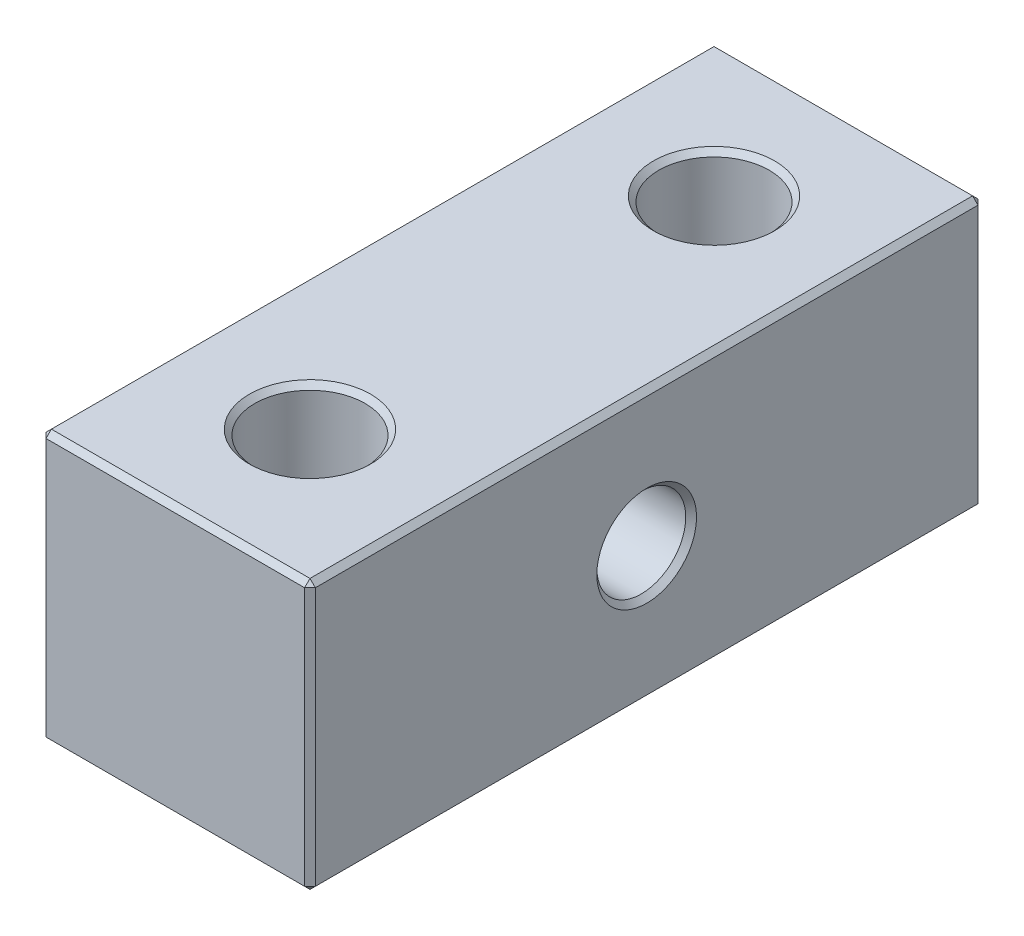
SolidWorks part; units mm, degrees
ref_plane "前视基准面" through (0, 0, 0) normal (0, 0, 1) x (1, 0, 0)
ref_plane "上视基准面" through (0, 0, 0) normal (0, 1, 0) x (1, 0, 0)
ref_plane "右视基准面" through (0, 0, 0) normal (1, 0, 0) x (0, 0, -1)
sketch "草图1" plane through (0, 0, 0) normal (0, 0, 1) x (1, 0, 0)
  line L1 (-5, 5) -> (5, 5)
  line L2 (-5, 5) -> (-5, -5)
  line L3 (-5, -5) -> (5, -5)
  line L4 (5, 5) -> (5, -5)
  line L5 (-5, 5) -> (5, -5) construction
  line L6 (-5, -5) -> (5, 5) construction
  point P0 (0, 0)
  dimension "D1" = 10
extrude "凸台-拉伸1" add sketch "草图1" along normal mid plane 25
hole_wizard "M4 螺纹孔1" positions "草图2" profile "草图3" tap size "M4" standard "GB" end condition through all
sketch "草图2" plane through (5, 0, 0) normal (1, 0, 0) x (0, 0, -1)
  line L0 (0, 0) -> (50000, 0) construction
  line L1 (12.5, -5) -> (12.5, 5) construction
  point P0 (0, 0)
  point P7 (0, 0)
  dimension "D1" = 12.5
sketch "草图3" plane through (5, 0, 0) normal (0, 1, 0) x (0, 0, -1)
  line L0 (0, 0) -> (0, 10)
  line L1 (0, 10) -> (1.65, 10)
  line L2 (1.65, 10) -> (1.65, 0)
  line L5 (1.65, 0) -> (0, 0)
  line L11 (0, -6.35) -> (0, 107.95) construction
  dimension "通孔螺纹孔钻头直径" = 3.3
  dimension "通孔螺纹孔钻头深度" = 10
cosmetic thread "孔螺蚊线3" parameters "D2"=4
hole_wizard "Ø4.1 (4.1) 直径孔1" positions "草图6" profile "草图7" hole size "Ø4.1" standard "GB" end condition through all
sketch "草图6" plane through (0, 5, 0) normal (0, 1, 0) x (1, 0, 0)
  line L0 (0, 0) -> (0, 50000) construction
  line L1 (0, 0) -> (50000, 0) construction
  point P0 (0, -7.5)
  point P2 (0, 7.5)
  point P11 (0, 0)
  point P12 (0, 0)
  point P15 (0, 0)
  dimension "D1" = 15
sketch "草图7" plane through (0, 5, 7.5) normal (1, 0, 0) x (0, 0, 1)
  line L0 (0, 0) -> (0, 10)
  line L1 (0, 10) -> (2.05, 10)
  line L2 (2.05, 10) -> (2.05, 0)
  line L5 (2.05, 0) -> (0, 0)
  line L11 (0, -6.35) -> (0, 107.95) construction
  dimension "通孔孔直径" = 4.1
  dimension "通孔孔深度" = 10
chamfer "倒角1" distance 0.2 angle 45 18 edges at (-5, 0, -1.65) (0, -5, 12.5) (0, -5, -12.5) (-5, -5, 0) (-5, 0, -12.5) (0, 5, 12.5) (-5, 5, 0) (0, 5, -12.5) (5, -5, 0) (5, 5, 0) (5, 0, -12.5) (5, 0, -1.65) (-5, 0, 12.5) (5, 0, 12.5) (0, -5, -5.45) (0, -5, 9.55) (0, 5, -5.45) (0, 5, 9.55)
